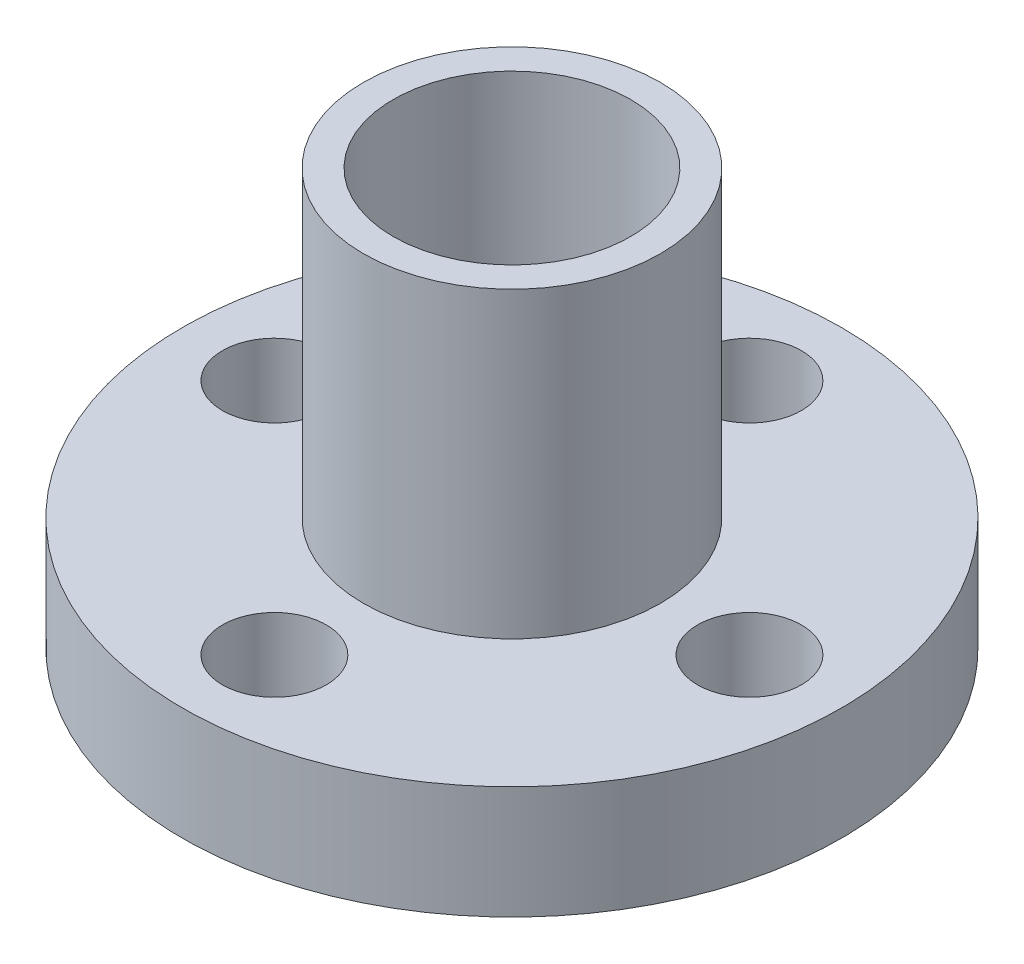
SolidWorks part; units mm, degrees
ref_plane "Front Plane" through (0, 0, 0) normal (0, 0, 1) x (1, 0, 0)
ref_plane "Top Plane" through (0, 0, 0) normal (0, 1, 0) x (1, 0, 0)
ref_plane "Right Plane" through (0, 0, 0) normal (1, 0, 0) x (0, 0, -1)
sketch "Sketch1" plane through (0, 0, 0) normal (0, 1, 0) x (1, 0, 0)
  circle A0 centre (0, 0) radius 11.1
  dimension "D1" = 22.2
extrude "Boss-Extrude1" add sketch "Sketch1" along normal blind 3.8
sketch "Sketch2" plane through (0, 3.8, 0) normal (0, 1, 0) x (1, 0, 0)
  circle A0 centre (0, 0) radius 5
  dimension "D1" = 10
extrude "Boss-Extrude2" add sketch "Sketch2" along normal blind 14 from surface at -3.8 starting at face at (0, 0, 11.1)
sketch "Sketch3" plane through (0, 14, 0) normal (0, 1, 0) x (1, 0, 0)
  circle A0 centre (0, 0) radius 4
  dimension "D1" = 8
extrude "Cut-Extrude1" cut sketch "Sketch3" against normal through all
sketch "Sketch4" plane through (0, 0, 0) normal (0, -1, 0) x (1, 0, 0)
  circle A0 centre (0, 0) radius 5.09
  circle A1 centre (0, 0) radius 4 construction
  circle A2 centre (0, 0) radius 4
  dimension "D1" = 10.18
extrude "Boss-Extrude3" add sketch "Sketch4" along normal blind 1.67
hole_wizard "Ø3.5 (3.5) Diameter Hole1" positions "Sketch5" profile "Sketch6" hole size "Ø3.5" standard "ISO" end condition through all
sketch "Sketch5" plane through (0, 3.8, 0) normal (0, 1, 0) x (1, 0, 0)
  circle A0 centre (0, 0) radius 8
  point P0 (0, 8)
  point P2 (0, -8)
  point P4 (8, 0)
  point P6 (-8, 0)
  dimension "D1" = 16
sketch "Sketch6" plane through (0, 3.8, -8) normal (1, 0, 0) x (0, 0, 1)
  line L0 (0, 0) -> (0, 5.47)
  line L1 (0, 5.47) -> (1.75, 5.47)
  line L2 (1.75, 5.47) -> (1.75, 0)
  line L5 (1.75, 0) -> (0, 0)
  line L11 (0, -6.35) -> (0, 107.95) construction
  dimension "Thru Hole Dia." = 3.5
  dimension "Thru Hole Depth" = 5.47
